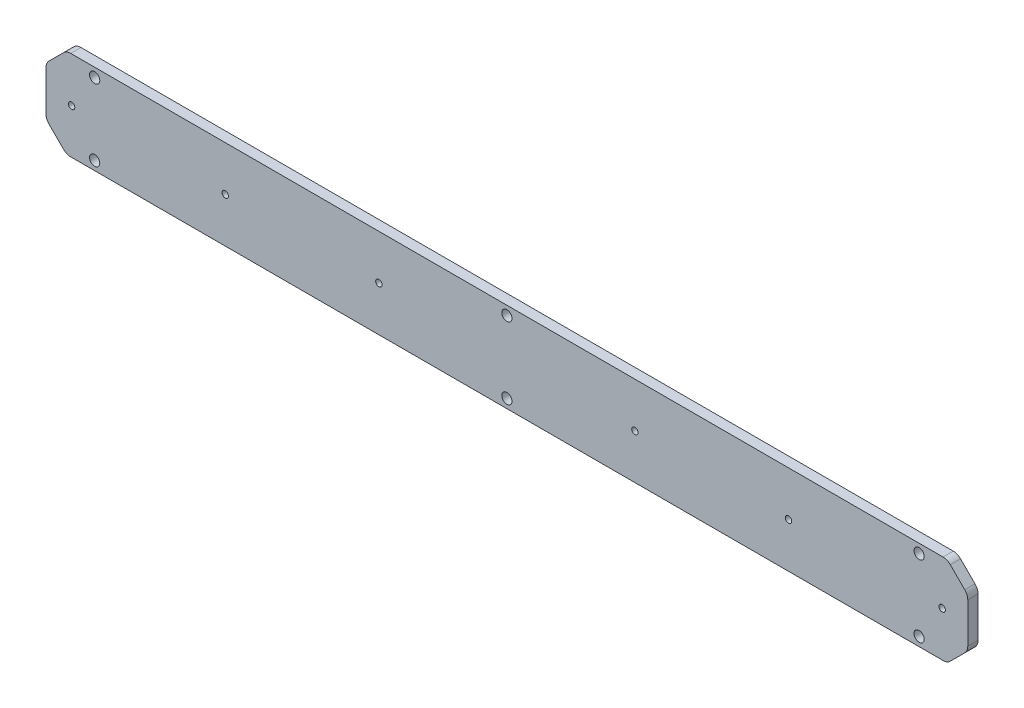
SolidWorks part; units mm, degrees
material "acero"
ref_plane "Alzado" through (0, 0, 0) normal (0, 0, 1) x (1, 0, 0)
ref_plane "Planta" through (0, 0, 0) normal (0, 1, 0) x (1, 0, 0)
ref_plane "Vista lateral" through (0, 0, 0) normal (1, 0, 0) x (0, 0, -1)
sketch "Croquis1" plane through (0, 0, 0) normal (0, 0, 1) x (1, 0, 0)
  line L0 (0, 14) -> (0, -14) construction
  line L1 (-180, -17.5) -> (180, -17.5)
  line L2 (-180, -17.5) -> (-180, 17.5)
  line L3 (-180, 17.5) -> (180, 17.5)
  line L4 (180, -17.5) -> (180, 17.5)
  line L5 (-180, -17.5) -> (180, 17.5) construction
  line L6 (-180, 17.5) -> (180, -17.5) construction
  circle A0 centre (0, 14) radius 1.6 construction
  circle A1 centre (0, -14) radius 1.6 construction
  point P0 (0, 0)
  dimension "D3" = 28
  dimension "D4" = 3.2
  dimension "D1" = 360
  dimension "D2" = 35
extrude "Saliente-Extruir1" add sketch "Croquis1" along normal blind 4
sketch "Croquis2" plane through (0, 0, 4) normal (0, 0, 1) x (1, 0, 0)
  line L0 (0, 0) -> (-161, 0) construction
  line L1 (0, 0) -> (161, 0) construction
  line L2 (161, 14) -> (161, -14) construction
  line L3 (-161, 14) -> (-161, -14) construction
  line L4 (0, 14) -> (0, -14) construction
  circle A0 centre (0, 14) radius 2
  circle A1 centre (0, -14) radius 2
  circle A2 centre (161, 14) radius 2
  circle A3 centre (161, -14) radius 2
  circle A4 centre (-161, 14) radius 2
  circle A5 centre (-161, -14) radius 2
  dimension "D1" = 4
  dimension "D2" = 161
  dimension "D4" = 28
extrude "Cortar-Extruir1" cut sketch "Croquis2" against normal blind 5
sketch "Croquis4" plane through (0, 0, 4) normal (0, 0, 1) x (1, 0, 0)
  line L0 (-161, 0) -> (0, 0) construction
  line L1 (0, 0) -> (161, 0) construction
  line L2 (161, 9) -> (161, -9) construction
  line L3 (0, 9) -> (0, -9) construction
  line L4 (-161, 9) -> (-161, -9) construction
  dimension "D1" = 161
  dimension "D2" = 18
hole_wizard "Perforador para roscar para macho de roscar para M41" [suppressed] positions "Croquis3D2" profile "Croquis5" hole size "M4" standard "Din"
sketch3d "Croquis3D2"
  point P0 (-161, 9, 4)
  point P3 (-161, -9, 4)
  point P6 (0, 9, 4)
  point P9 (0, -9, 4)
  point P12 (161, 9, 4)
  point P15 (161, -9, 4)
sketch "Croquis5" plane through (-161, 9, 4) normal (1, 0, 0) x (0, -1, 0)
  line L0 (0, 0) -> (0, 4)
  line L1 (0, 4) -> (1.65, 4)
  line L2 (1.65, 4) -> (1.65, 0)
  line L5 (1.65, 0) -> (0, 0)
  line L11 (0, -6.35) -> (0, 107.95) construction
  dimension "Diámetro de taladro hasta el siguiente" = 3.3
  dimension "Profundidad de taladro hasta el siguiente" = 4
cosmetic thread "Rosca cosmética1" [suppressed] parameters "D2"=4
cosmetic thread "Rosca cosmética2" [suppressed] parameters "D2"=4
cosmetic thread "Rosca cosmética3" [suppressed] parameters "D2"=4
cosmetic thread "Rosca cosmética4" [suppressed] parameters "D2"=4
cosmetic thread "Rosca cosmética5" [suppressed] parameters "D2"=4
cosmetic thread "Rosca cosmética6" [suppressed] parameters "D2"=4
sketch "Croquis6" plane through (0, 0, 4) normal (0, 0, 1) x (1, 0, 0)
  line L0 (-10, 0) -> (-170, 0) construction
  line L1 (-161, 0) -> (0, 0) construction
  line L2 (-10, 0) -> (170, 0) construction
  line L3 (-10, 0) -> (-50, 0) construction
  line L4 (-10, 0) -> (50, 0) construction
  line L5 (-50, 0) -> (-110, 0) construction
  line L6 (50, 0) -> (110, 0) construction
  dimension "D1" = 10
  dimension "D2" = 180
  dimension "D3" = 160
  dimension "D4" = 40
  dimension "D5" = 60
  dimension "D6" = 60
  dimension "D7" = 60
hole_wizard "Taladro roscado M31" positions "Croquis7" profile "Croquis9" tap size "M3" standard "ISO" end condition through all
sketch "Croquis7" plane through (0, 0, 4) normal (0, 0, 1) x (1, 0, 0)
  point P0 (-170, 0)
  point P5 (-110, 0)
  point P8 (-50, 0)
  point P11 (50, 0)
  point P14 (110, 0)
  point P17 (170, 0)
sketch "Croquis9" plane through (-170, 0, 4) normal (1, 0, 0) x (0, -1, 0)
  line L0 (0, 0) -> (0, 4)
  line L1 (0, 4) -> (1.25, 4)
  line L2 (1.25, 4) -> (1.25, 0)
  line L5 (1.25, 0) -> (0, 0)
  line L11 (0, -6.35) -> (0, 107.95) construction
  dimension "Diámetro de perforador para roscar hasta el siguiente" = 2.5
  dimension "Profundidad de perforador para roscar hasta el siguiente" = 4
cosmetic thread "Rosca de taladro1" parameters "D2"=3
cosmetic thread "Rosca de taladro2" parameters "D2"=3
cosmetic thread "Rosca de taladro3" parameters "D2"=3
cosmetic thread "Rosca de taladro4" parameters "D2"=3
cosmetic thread "Rosca de taladro5" parameters "D2"=3
cosmetic thread "Rosca de taladro6" parameters "D2"=3
chamfer "Chaflán1" distance 8 angle 45 4 edges at (180, -17.5, 2) (180, 17.5, 2) (-180, -17.5, 2) (-180, 17.5, 2)
fillet "Redondeo2" radius 4 8 edges at (-172, -17.5, 2) (-180, -9.5, 2) (-180, 9.5, 2) (-172, 17.5, 2) (172, -17.5, 2) (180, -9.5, 2) (180, 9.5, 2) (172, 17.5, 2)
